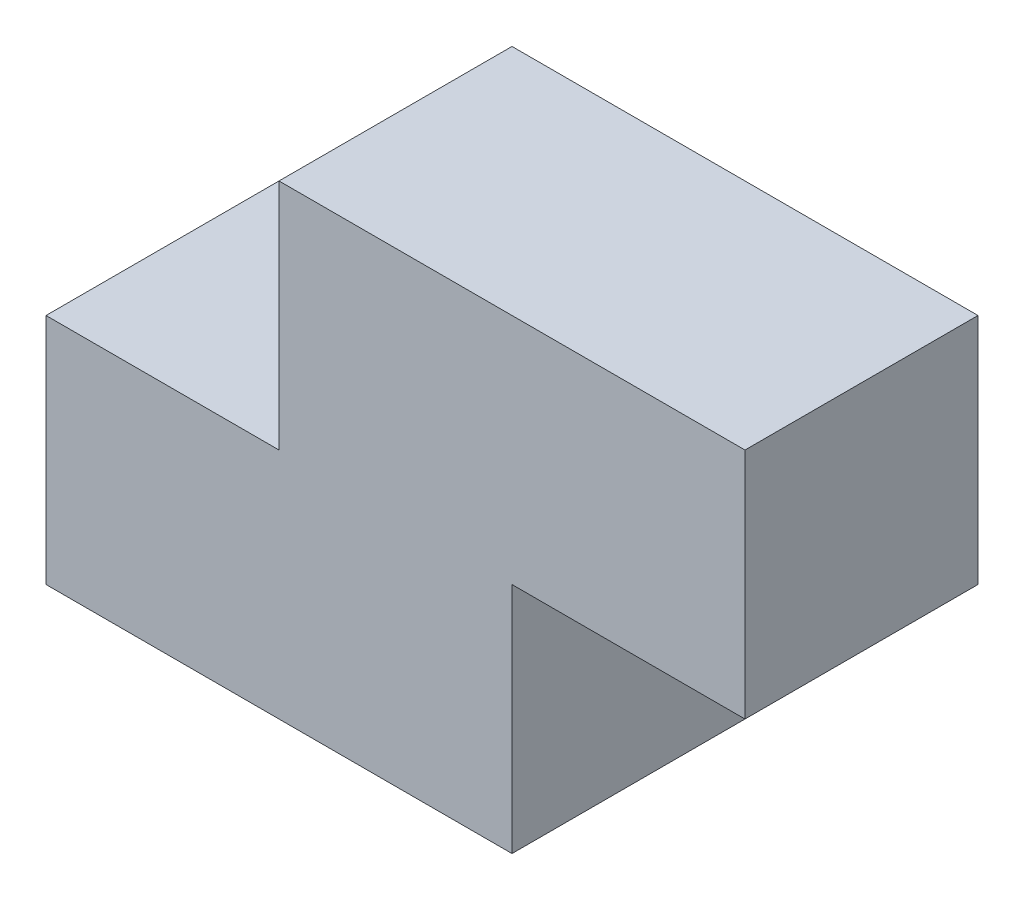
SolidWorks part; units mm, degrees
ref_plane "Plan de face" through (0, 0, 0) normal (0, 0, 1) x (1, 0, 0)
ref_plane "Plan de dessus" through (0, 0, 0) normal (0, 1, 0) x (1, 0, 0)
ref_plane "Plan de droite" through (0, 0, 0) normal (1, 0, 0) x (0, 0, -1)
sketch "Esquisse1" plane through (0, 0, 0) normal (0, 0, 1) x (1, 0, 0)
  line L0 (0, 0) -> (600, 0)
  line L1 (600, 0) -> (600, 300)
  line L2 (600, 300) -> (900, 300)
  line L3 (900, 300) -> (900, 600)
  line L4 (900, 600) -> (300, 600)
  line L5 (300, 600) -> (300, 300)
  line L6 (300, 300) -> (0, 300)
  line L7 (0, 300) -> (0, 0)
  dimension "D1" = 300
  dimension "D2" = 300
  dimension "D3" = 600
  dimension "D4" = 900
  dimension "D5" = 600
  dimension "D6" = 300
extrude "Boss.-Extru.1" add sketch "Esquisse1" along normal blind 300
